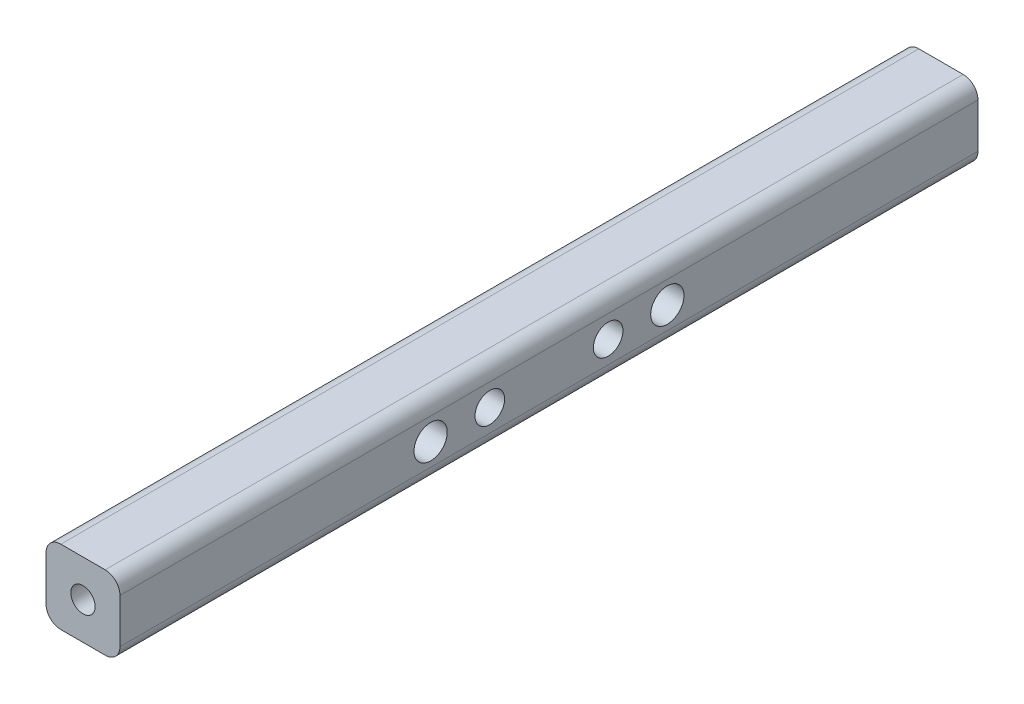
SolidWorks part; units mm, degrees
material "Alliage 1060"
ref_plane "Face" through (0, 0, 0) normal (0, 0, 1) x (1, 0, 0)
ref_plane "Dessus" through (0, 0, 0) normal (0, 1, 0) x (1, 0, 0)
ref_plane "Droite" through (0, 0, 0) normal (1, 0, 0) x (0, 0, -1)
sketch "Esquisse1" plane through (0, 0, 0) normal (0, 0, 1) x (1, 0, 0)
  line L1 (-5, 5) -> (5, 5)
  line L2 (-5, 5) -> (-5, -5)
  line L3 (-5, -5) -> (5, -5)
  line L4 (5, 5) -> (5, -5)
  dimension "D1" = 5
  dimension "D2" = 5
extrude "Boss.-Extru.1" add sketch "Esquisse1" along normal mid plane 116
fillet "Congé1" radius 2 4 edges at (-5, -5, 0) (5, -5, 0) (5, 5, 0) (-5, 5, 0)
hole_wizard "Trou taraudé M41" positions "Esquisse14" profile "Esquisse13" tap size "M4" standard "Iso"
sketch "Esquisse14" plane through (0, 0, 58) normal (0, 0, 1) x (1, 0, 0)
  point P0 (0, 0)
sketch "Esquisse13" plane through (0, 0, 58) normal (1, 0, 0) x (0, -1, 0)
  line L0 (0, 0) -> (0, 12.4914)
  line L1 (0, 12.4914) -> (1.65, 11.5)
  line L2 (1.65, 11.5) -> (1.65, 0)
  line L5 (1.65, 0) -> (0, 0)
  line L10 (0, 12.4914) -> (-1.65, 11.5) construction
  line L11 (0, -6.35) -> (0, 107.95) construction
  dimension "Diamètre du trou pour taraudage" = 3.3
  dimension "Profondeur du trou pour taraudage" = 11.5
  dimension "Angle de pointe" = 118
cosmetic thread "Filetage de perçage1" parameters "D1"=8, "D2"=4
hole_wizard "Trou taraudé M42" positions "Esquisse16" profile "Esquisse15" tap size "M4" standard "Iso"
sketch "Esquisse16" plane through (0, 0, -58) normal (0, 0, -1) x (-1, 0, 0)
  point P0 (0, 0)
sketch "Esquisse15" plane through (0, 0, -58) normal (1, 0, 0) x (0, 1, 0)
  line L0 (0, 0) -> (0, 12.4914)
  line L1 (0, 12.4914) -> (1.65, 11.5)
  line L2 (1.65, 11.5) -> (1.65, 0)
  line L5 (1.65, 0) -> (0, 0)
  line L10 (0, 12.4914) -> (-1.65, 11.5) construction
  line L11 (0, -6.35) -> (0, 107.95) construction
  dimension "Diamètre du trou pour taraudage" = 3.3
  dimension "Profondeur du trou pour taraudage" = 11.5
  dimension "Angle de pointe" = 118
cosmetic thread "Filetage de perçage2" parameters "D1"=8, "D2"=4
hole_wizard "Diamètre du perçage Ø4.0 (4)1" positions "Esquisse20" profile "Esquisse19" hole size "Ø4.0" standard "Din"
sketch "Esquisse20" plane through (5, 0, 0) normal (1, 0, 0) x (0, 0, -1)
  point P0 (8, 0)
  point P2 (-8, 0)
  dimension "D1" = 8
  dimension "D2" = 8
sketch "Esquisse19" plane through (5, 0, -8) normal (0, 1, 0) x (0, 0, -1)
  line L0 (0, 0) -> (0, 6.2017)
  line L1 (0, 6.2017) -> (2, 5)
  line L2 (2, 5) -> (2, 0)
  line L5 (2, 0) -> (0, 0)
  line L10 (0, 6.2017) -> (-2, 5) construction
  line L11 (0, -6.35) -> (0, 107.95) construction
  dimension "Diamètre du perçage" = 4
  dimension "Profondeur du perçage" = 5
  dimension "Angle de pointe" = 118
hole_wizard "Chambrage pour vis à tête hexagonale M41" positions "Esquisse22" profile "Esquisse21" counterbore size "M4" standard "Iso" end condition through all
sketch "Esquisse22" plane through (-5, 0, 0) normal (-1, 0, 0) x (0, 0, 1)
  point P0 (-16, 0)
  point P2 (16, 0)
  dimension "D1" = 16
  dimension "D2" = 16
sketch "Esquisse21" plane through (-5, 0, -16) normal (0, 1, 0) x (0, 0, 1)
  line L0 (0, 0) -> (0, 10)
  line L1 (0, 10) -> (2.25, 10)
  line L3 (2.25, 10) -> (2.25, 5)
  line L4 (2.25, 5) -> (4, 5)
  line L5 (4, 5) -> (4, 0)
  line L7 (4, 0) -> (0, 0)
  line L11 (0, -6.35) -> (0, 107.95) construction
  dimension "Diamètre du perçage jusqu'au prochain" = 4.5
  dimension "Profondeur du perçage jusqu'au prochain" = 10
  dimension "Diamètre du chambrage" = 8
  dimension "Profondeur du chambrage" = 5
sketch "Esquisse23" plane through (5, 0, 0) normal (1, 0, 0) x (0, 0, -1)
  line L1 (-20, 6) -> (20, 6)
  line L2 (-20, 6) -> (-20, -6)
  line L3 (-20, -6) -> (20, -6)
  line L4 (20, 6) -> (20, -6)
  dimension "D1" = 20
  dimension "D2" = 20
extrude "Enlèv. mat.-Extru.1" [suppressed] cut sketch "Esquisse23" against normal blind 3
